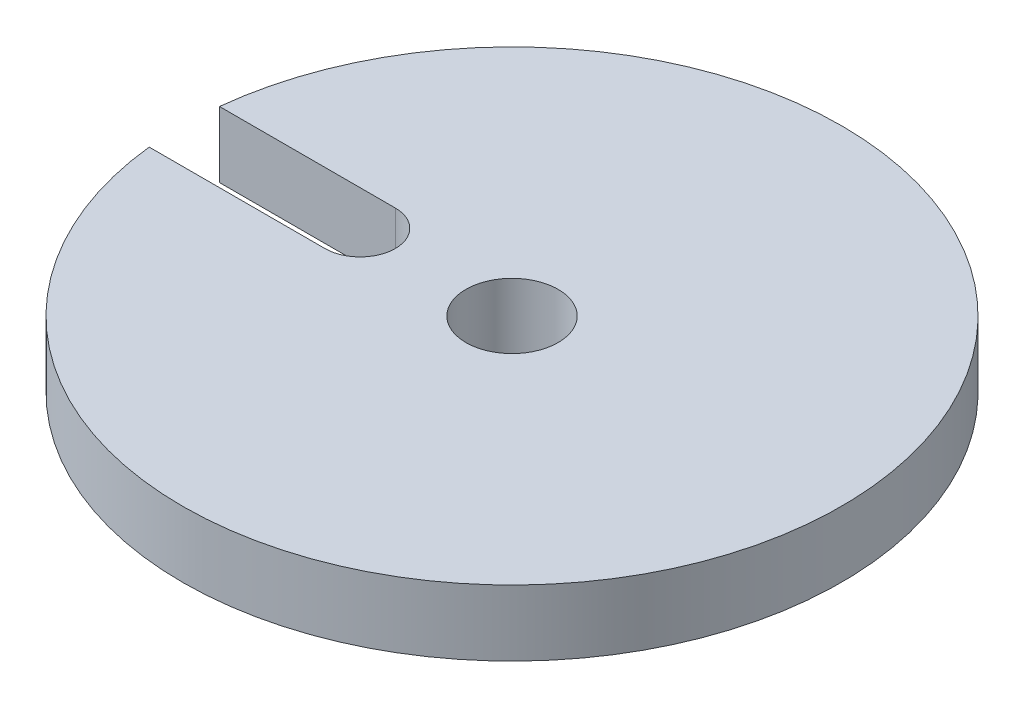
SolidWorks part; units mm, degrees
material "ABS"
ref_plane "正面" through (0, 0, 0) normal (0, 0, 1) x (1, 0, 0)
ref_plane "平面" through (0, 0, 0) normal (0, 1, 0) x (1, 0, 0)
ref_plane "右側面" through (0, 0, 0) normal (1, 0, 0) x (0, 0, -1)
sketch "ｽｹｯﾁ1" plane through (0, 0, 0) normal (0, 1, 0) x (1, 0, 0)
  circle A0 centre (0, 0) radius 2.1
  circle A1 centre (0, 0) radius 15
  dimension "D1" = 30
  dimension "D2" = 4.2
extrude "ﾎﾞｽ - 押し出し1" add sketch "ｽｹｯﾁ1" along normal blind 3
sketch "ｽｹｯﾁ2" plane through (0, 3, 0) normal (0, 1, 0) x (1, 0, 0)
  line L1 (-14.9144, 1.6) -> (-6.9144, 1.6)
  line L2 (-14.9144, 1.6) -> (-14.9144, -1.6) construction
  line L3 (-14.9144, -1.6) -> (-6.9144, -1.6)
  line L4 (-6.9144, 1.6) -> (-6.9144, -1.6) construction
  circle A0 centre (0, 0) radius 15 construction
  arc A1 (-6.9144, 1.6) -> (-6.9144, -1.6) centre (-6.9144, 0) cw
  arc A2 (-14.9144, 1.6) -> (-14.9144, -1.6) centre (-14.9144, 0) ccw
  dimension "D1" = 3.2
  dimension "D2" = 8
extrude "ｶｯﾄ - 押し出し1" cut sketch "ｽｹｯﾁ2" against normal blind 10
